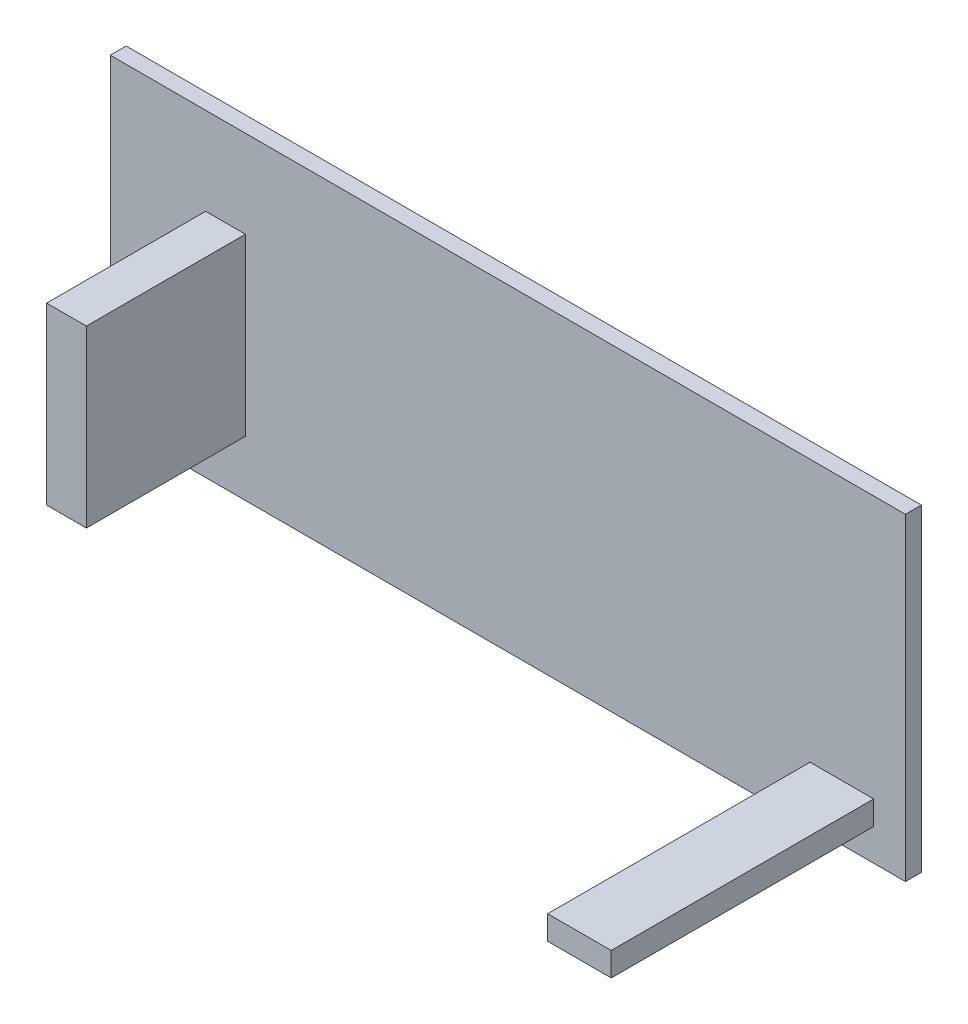
SolidWorks part; units mm, degrees
ref_plane "Plan de face" through (0, 0, 0) normal (0, 0, 1) x (1, 0, 0)
ref_plane "Plan de dessus" through (0, 0, 0) normal (0, 1, 0) x (1, 0, 0)
ref_plane "Plan de droite" through (0, 0, 0) normal (1, 0, 0) x (0, 0, -1)
sketch "Esquisse1" plane through (0, 0, 0) normal (0, 0, 1) x (1, 0, 0)
  line L1 (-50, 20) -> (50, 20)
  line L2 (-50, 20) -> (-50, -20)
  line L3 (-50, -20) -> (50, -20)
  line L4 (50, 20) -> (50, -20)
  dimension "D1" = 100
  dimension "D2" = 40
  dimension "D3" = 20
  dimension "D4" = 50
extrude "Boss.-Extru.1" add sketch "Esquisse1" along normal blind 2
sketch "Esquisse3" plane through (0, 0, 2) normal (0, 0, 1) x (1, 0, 0)
  line L0 (-50, 20) -> (-50, -20) construction
  line L1 (-38, 9) -> (-33, 9)
  line L2 (-38, 9) -> (-38, -13)
  line L3 (-38, -13) -> (-33, -13)
  line L4 (-33, 9) -> (-33, -13)
  line L5 (-50, -20) -> (50, -20) construction
  dimension "D1" = 5
  dimension "D2" = 22
  dimension "D3" = 12
  dimension "D4" = 7
extrude "Boss.-Extru.2" add sketch "Esquisse3" along normal blind 20
sketch "Esquisse4" plane through (0, 0, 0) normal (0, 0, 1) x (1, 0, 0)
  line L0 (50, -20) -> (50, 20) construction
  line L1 (38, -13) -> (46, -13)
  line L2 (38, -13) -> (38, -16)
  line L3 (38, -16) -> (46, -16)
  line L4 (46, -13) -> (46, -16)
  line L5 (-50, -20) -> (50, -20) construction
  dimension "D1" = 4
  dimension "D2" = 3
  dimension "D3" = 8
  dimension "D4" = 4
extrude "Boss.-Extru.3" add sketch "Esquisse4" along normal blind 35
